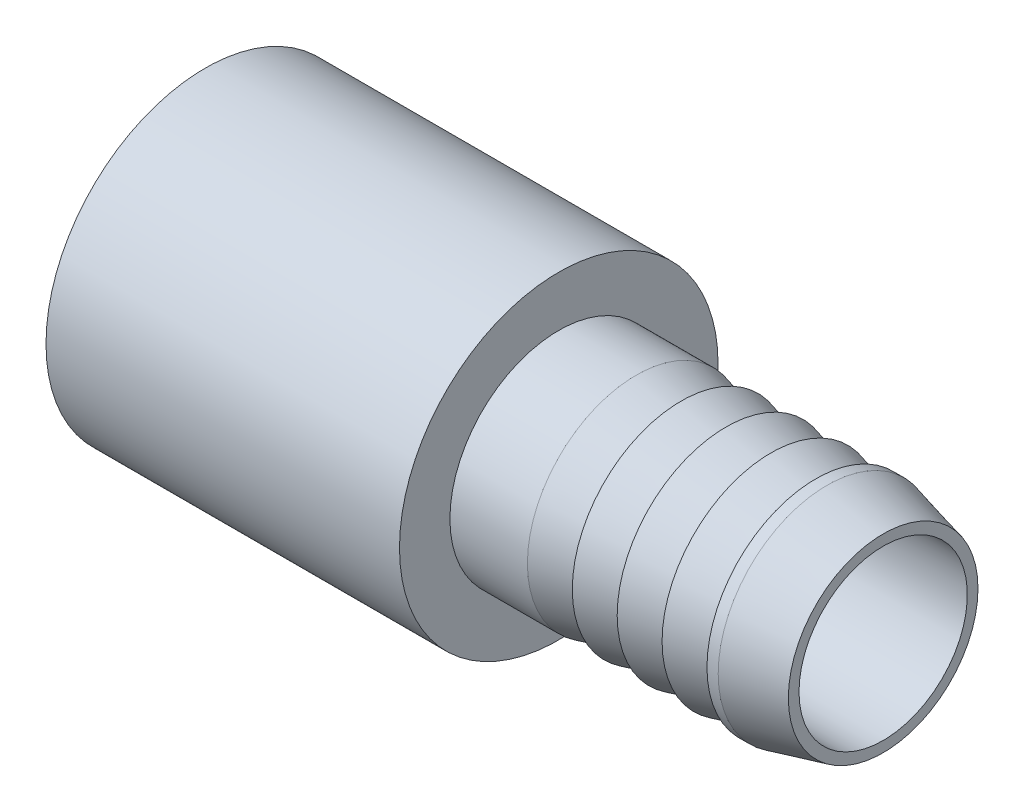
SolidWorks part; units mm, degrees
ref_plane "Plan de face" through (0, 0, 0) normal (0, 0, 1) x (1, 0, 0)
ref_plane "Plan de dessus" through (0, 0, 0) normal (0, 1, 0) x (1, 0, 0)
ref_plane "Plan de droite" through (0, 0, 0) normal (1, 0, 0) x (0, 0, -1)
ref_plane "Plan1"
sketch "Esquisse1" plane through (0, 0, 0) normal (0, 0, 1) x (1, 0, 0)
  line L0 (-19.304, 5.08) -> (19.05, 5.08)
  line L1 (19.05, 5.08) -> (19.05, 6.477)
  line L2 (19.05, 6.477) -> (15.24, 6.477)
  line L3 (15.24, 6.477) -> (15.24, 5.842)
  line L4 (15.24, 5.842) -> (12.7, 6.477)
  line L5 (12.7, 6.477) -> (12.7, 5.842)
  line L6 (12.7, 5.842) -> (10.16, 6.477)
  line L7 (10.16, 6.477) -> (10.16, 5.842)
  line L8 (10.16, 5.842) -> (7.62, 6.477)
  line L9 (7.62, 6.477) -> (7.62, 5.842)
  line L10 (7.62, 5.842) -> (5.08, 6.477)
  line L11 (5.08, 6.477) -> (0.696, 6.477)
  line L12 (0.696, 6.477) -> (0.696, 9.33)
  line L13 (0.696, 9.33) -> (-19.304, 9.33)
  line L14 (-19.304, 9.33) -> (-19.304, 5.08)
  line L15 (0, 0.3175) -> (142.9139, 0.3175) construction
  dimension "D1" = 4.7625
  dimension "D2" = 38.354
  dimension "D3" = 3.81
  dimension "D4" = 2.54
  dimension "D5" = 2.54
  dimension "D6" = 2.54
  dimension "D7" = 2.54
  dimension "D8" = 165.964
  dimension "D9" = 38.354
  dimension "D10" = 38.354
  dimension "D11" = 20
  dimension "D12" = 4.25
revolve "Revolution1" add sketch "Esquisse1" angle 360 about L15
chamfer "Chamfer1" distance 0.7938 distance2 3.175 1 edges at (19.05, 0.3175, 6.1595)
ref_plane "Plan2"
sketch "Esquisse2" plane through (0, 0, 0) normal (-1, 0, 0) x (0, 0, 1)
  line L0 (0.3759, -9.1577) -> (-7.7429, -4.9044)
  line L1 (-7.7429, -4.9044) -> (-8.1188, 4.2533)
  line L2 (-8.1188, 4.2533) -> (-0.3759, 9.1577)
  line L3 (-0.3759, 9.1577) -> (7.7429, 4.9044)
  line L4 (7.7429, 4.9044) -> (8.1188, -4.2533)
  line L5 (8.1188, -4.2533) -> (0.3759, -9.1577)
  dimension "D1" = 15.875
